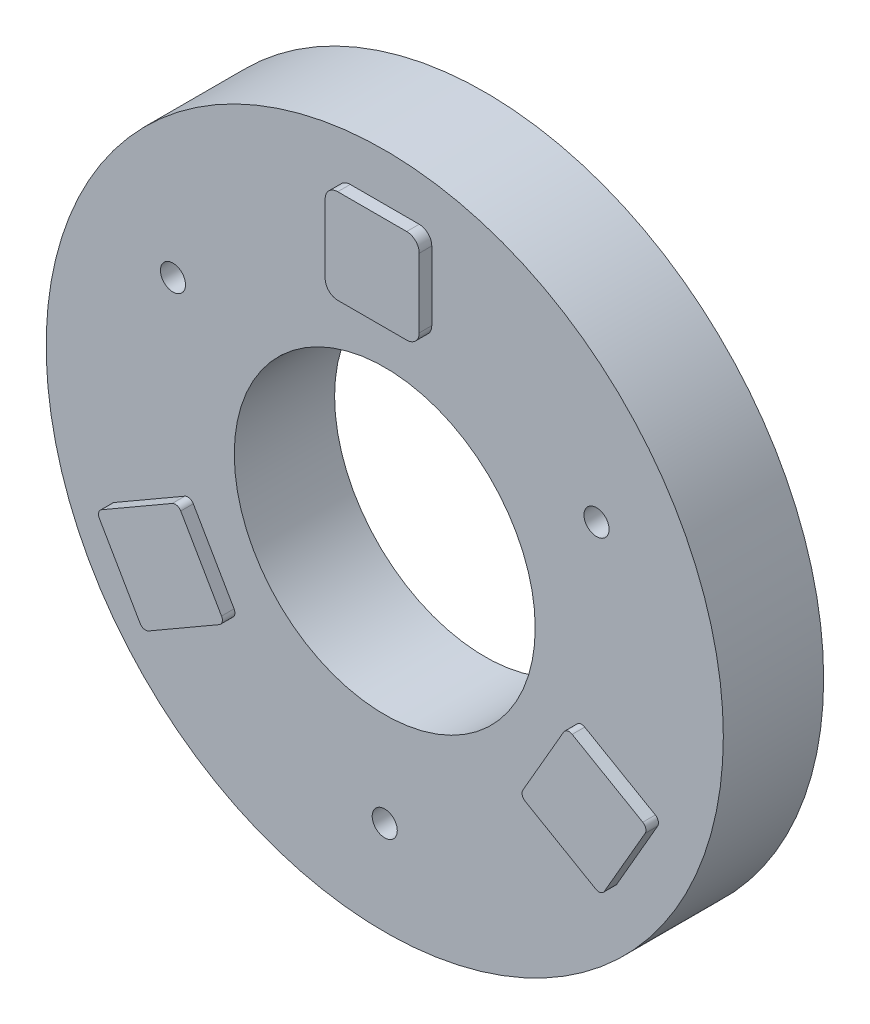
SolidWorks part; units mm, degrees
material "Alloy Steel"
ref_plane "Front Plane" through (0, 0, 0) normal (0, 0, 1) x (1, 0, 0)
ref_plane "Top Plane" through (0, 0, 0) normal (0, 1, 0) x (1, 0, 0)
ref_plane "Right Plane" through (0, 0, 0) normal (1, 0, 0) x (0, 0, -1)
sketch "Sketch2" plane through (0, 0, 0) normal (0, 0, 1) x (1, 0, 0)
  line L0 (0, 0) -> (0, 6) construction
  line L1 (0, 6) -> (0, 9.75) construction
  line L2 (0, 9.75) -> (0, 13.5) construction
  line L3 (0, 0) -> (11.6913, 6.75) construction
  line L4 (1.875, 11.625) -> (-1.875, 11.625) construction
  line L5 (1.875, 11.625) -> (1.875, 7.875) construction
  line L6 (1.875, 7.875) -> (-1.875, 7.875) construction
  line L7 (-1.875, 11.625) -> (-1.875, 7.875) construction
  line L8 (1.875, 11.625) -> (-1.875, 7.875) construction
  line L9 (1.875, 7.875) -> (-1.875, 11.625) construction
  line L10 (0, 0) -> (-8.4437, 4.875) construction
  line L11 (0, 0) -> (0, -9.75) construction
  circle A0 centre (0, 0) radius 13.5
  circle A1 centre (0, 0) radius 6
  circle A2 centre (0, 0) radius 9.75 construction
  circle A3 centre (8.4437, 4.875) radius 0.5
  circle A4 centre (0, -9.75) radius 0.5
  circle A5 centre (-8.4437, 4.875) radius 0.5
  point P14 (0, 11.625)
  point P22 (0, 0)
  dimension "D1" = 27
  dimension "D2" = 12
  dimension "D4" = 1
  dimension "D3" = 60
  dimension "D6" = 120
  dimension "D5" = 3
extrude "Boss-Extrude2" add sketch "Sketch2" along normal mid plane 4
sketch "Sketch3" plane through (0, 0, 0) normal (0, 0, 1) x (1, 0, 0)
  line L0 (7.6325, -2.5302) -> (6.0075, -5.3448)
  line L1 (-1.375, 7.875) -> (1.375, 7.875)
  line L2 (-1.875, 8.375) -> (-1.875, 11.125)
  line L3 (-1.375, 11.625) -> (1.375, 11.625)
  line L4 (1.875, 8.375) -> (1.875, 11.125)
  line L5 (-1.875, 7.875) -> (1.875, 11.625) construction
  line L6 (-1.875, 11.625) -> (1.875, 7.875) construction
  line L7 (7.974, -2.4387) -> (10.7885, -4.0637)
  line L8 (10.88, -4.4052) -> (9.255, -7.2198)
  line L9 (6.099, -5.6863) -> (8.9135, -7.3113)
  line L10 (7.7575, -2.3137) -> (9.13, -7.4363) construction
  line L11 (11.005, -4.1887) -> (5.8825, -5.5613) construction
  line L12 (-6.0075, -5.3448) -> (-7.6325, -2.5302)
  line L13 (-6.099, -5.6863) -> (-8.9135, -7.3113)
  line L14 (-9.255, -7.2198) -> (-10.88, -4.4052)
  line L15 (-7.974, -2.4387) -> (-10.7885, -4.0637)
  line L16 (-5.8825, -5.5613) -> (-11.005, -4.1887) construction
  line L17 (-9.13, -7.4363) -> (-7.7575, -2.3137) construction
  line L18 (-8.4437, -4.875) -> (0, 0) construction
  line L19 (0, 0) -> (8.4437, -4.875) construction
  line L20 (0, 0) -> (0, 6) construction
  arc A0 (1.375, 11.625) -> (1.875, 11.125) centre (1.375, 11.125) cw
  arc A1 (1.375, 7.875) -> (1.875, 8.375) centre (1.375, 8.375) ccw
  arc A2 (-1.375, 7.875) -> (-1.875, 8.375) centre (-1.375, 8.375) cw
  arc A3 (-1.875, 11.125) -> (-1.375, 11.625) centre (-1.375, 11.125) cw
  arc A4 (9.255, -7.2198) -> (8.9135, -7.3113) centre (9.0385, -7.0948) cw
  arc A5 (10.7885, -4.0637) -> (10.88, -4.4052) centre (10.6635, -4.2802) cw
  arc A6 (7.6325, -2.5302) -> (7.974, -2.4387) centre (7.849, -2.6552) cw
  arc A7 (6.0075, -5.3448) -> (6.099, -5.6863) centre (6.224, -5.4698) ccw
  arc A8 (-8.9135, -7.3113) -> (-9.255, -7.2198) centre (-9.0385, -7.0948) cw
  arc A9 (-6.0075, -5.3448) -> (-6.099, -5.6863) centre (-6.224, -5.4698) cw
  arc A10 (-7.6325, -2.5302) -> (-7.974, -2.4387) centre (-7.849, -2.6552) ccw
  arc A11 (-10.88, -4.4052) -> (-10.7885, -4.0637) centre (-10.6635, -4.2802) cw
  point P0 (0, 9.75)
  point P9 (8.4437, -4.875)
  point P14 (-8.4437, -4.875)
  point P19 (0, 0)
  dimension "D4" = 0.5
  dimension "D5" = 0.25
  dimension "D2" = 120
  dimension "D3" = 120
  dimension "D1" = 3
extrude "Boss-Extrude3" add sketch "Sketch3" along normal mid plane 5
equation "\"OrificeDiameter\"= 1"
equation "\"D4@Sketch2\"=\"OrificeDiameter\""
equation "\"InnerHousingDiameter\"= 27"
equation "\"D1@Sketch2\"=\"InnerHousingDiameter\""
